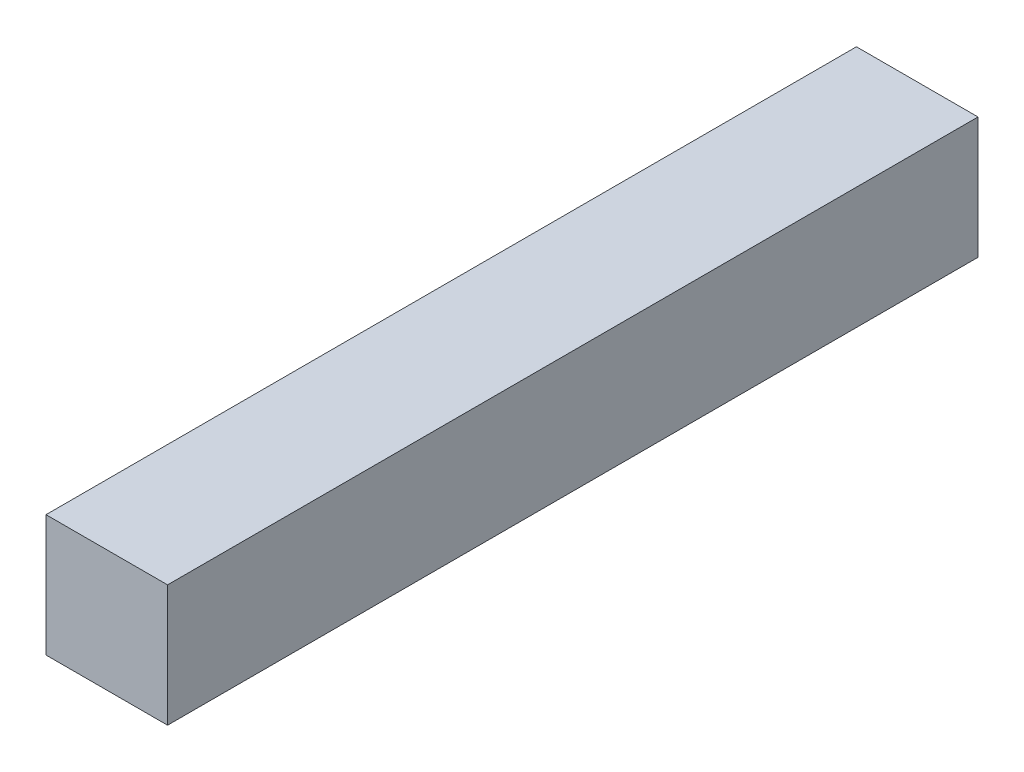
SolidWorks part; units mm, degrees
ref_plane "Front Plane" through (0, 0, 0) normal (0, 0, 1) x (1, 0, 0)
ref_plane "Top Plane" through (0, 0, 0) normal (0, 1, 0) x (1, 0, 0)
ref_plane "Right Plane" through (0, 0, 0) normal (1, 0, 0) x (0, 0, -1)
sketch "Sketch1" plane through (0, 0, 0) normal (0, 0, 1) x (1, 0, 0)
  line L1 (0, 0) -> (-7.62, 0)
  line L2 (0, 0) -> (0, 7.62)
  line L3 (0, 7.62) -> (-7.62, 7.62)
  line L4 (-7.62, 0) -> (-7.62, 7.62)
  dimension "D1" = 7.62
  dimension "D2" = 7.62
extrude "Boss-Extrude1" add sketch "Sketch1" along normal blind 50.8
